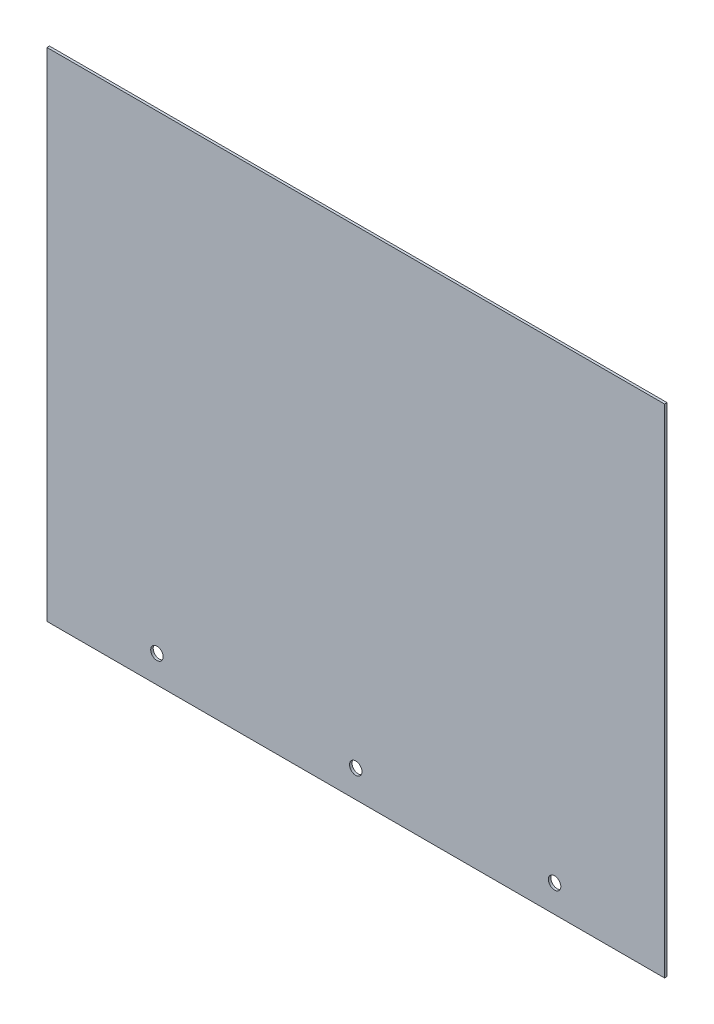
SolidWorks part; units mm, degrees
ref_plane "정면" through (0, 0, 0) normal (0, 0, 1) x (1, 0, 0)
ref_plane "윗면" through (0, 0, 0) normal (0, 1, 0) x (1, 0, 0)
ref_plane "우측면" through (0, 0, 0) normal (1, 0, 0) x (0, 0, -1)
sketch "스케치1" plane through (0, 0, 0) normal (0, 0, 1) x (1, 0, 0)
  line L0 (-47.4949, 100) -> (294.4085, 100) construction
  line L1 (0, 0) -> (248.5, 0)
  line L2 (0, 0) -> (0, 200)
  line L3 (0, 200) -> (248.5, 200)
  line L4 (248.5, 0) -> (248.5, 200)
  line L5 (33.8052, 11) -> (223.6828, 11) construction
  line L6 (124.25, 229.0993) -> (124.25, -73.1413) construction
  circle A0 centre (124.25, 11) radius 2.5
  circle A1 centre (204.25, 11) radius 2.5
  circle A2 centre (44.25, 11) radius 2.5
  dimension "D6" = 5
  dimension "D7" = 80
  dimension "D8" = 80
  dimension "D1" = 248.5
  dimension "D2" = 200
  dimension "D3" = 124.25
  dimension "D4" = 100
  dimension "D5" = 11
extrude "보스-돌출1" add sketch "스케치1" along normal mid plane 1
